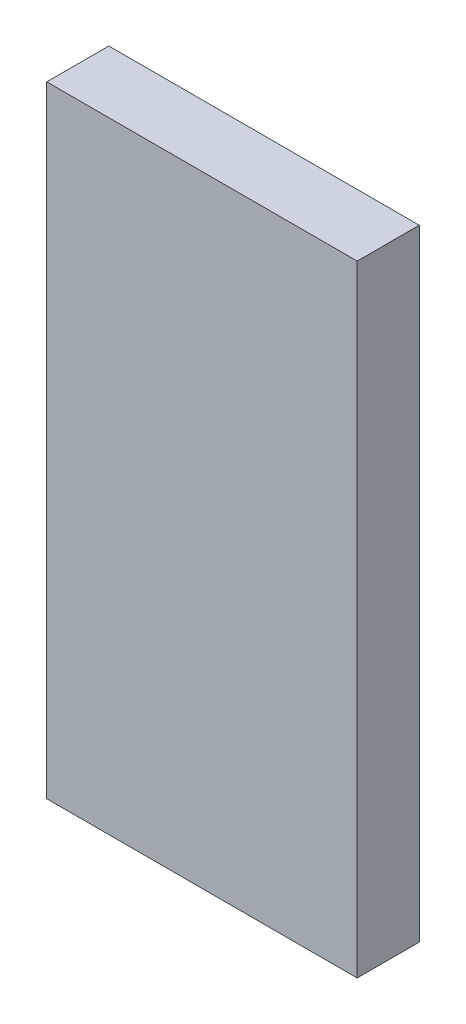
SolidWorks part; units mm, degrees
ref_plane "Front Plane" through (0, 0, 0) normal (0, 0, 1) x (1, 0, 0)
ref_plane "Top Plane" through (0, 0, 0) normal (0, 1, 0) x (1, 0, 0)
ref_plane "Right Plane" through (0, 0, 0) normal (1, 0, 0) x (0, 0, -1)
sketch "Sketch1" plane through (0, 0, 0) normal (0, 0, 1) x (1, 0, 0)
  line L0 (0, 0) -> (0, 25.4)
  line L1 (0, 25.4) -> (12.7, 25.4)
  line L2 (12.7, 25.4) -> (12.7, 0)
  line L3 (12.7, 0) -> (0, 0)
  dimension "D1" = 12.7
  dimension "D2" = 25.4
extrude "Boss-Extrude1" add sketch "Sketch1" along normal blind 2.54
sketch "Sketch2" plane through (12.7, 0, 0) normal (1, 0, 0) x (0, 0, -1)
  line L0 (-1.27, 25.4) -> (-1.27, 22.225)
  line L1 (-2.54, 25.4) -> (0, 25.4) construction
  circle A0 centre (-1.27, 22.225) radius 0.254
  dimension "D2" = 0.508
  dimension "D1" = 3.175
